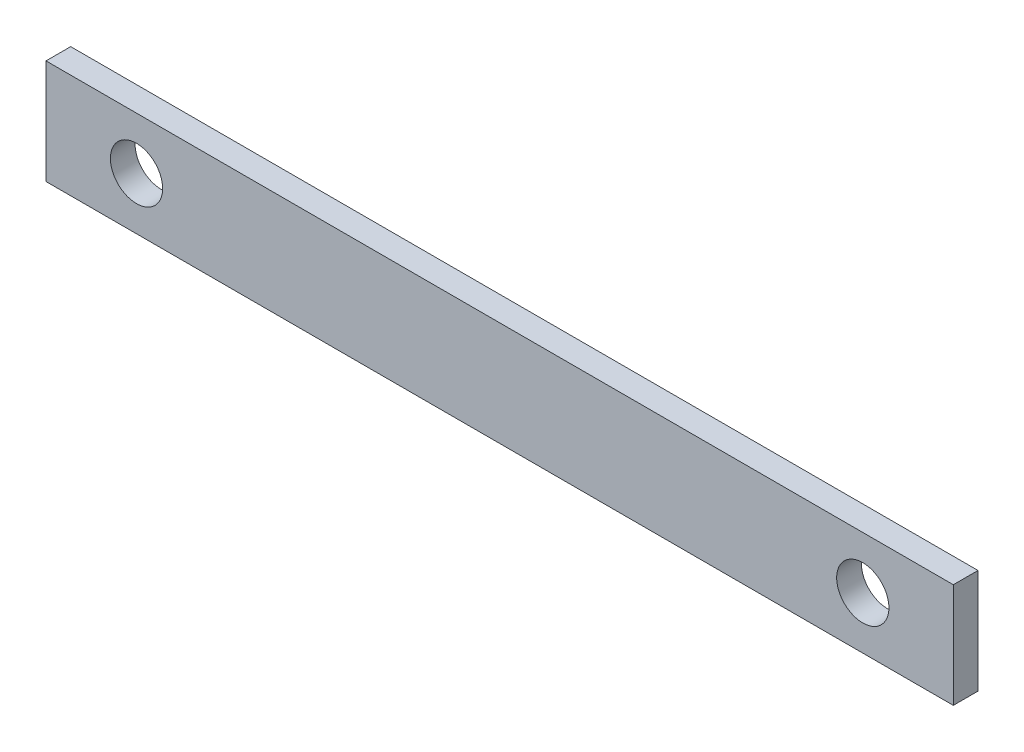
SolidWorks part; units mm, degrees
ref_plane "Alzado" through (0, 0, 0) normal (0, 0, 1) x (1, 0, 0)
ref_plane "Planta" through (0, 0, 0) normal (0, 1, 0) x (1, 0, 0)
ref_plane "Vista lateral" through (0, 0, 0) normal (1, 0, 0) x (0, 0, -1)
sketch "Croquis1" plane through (0, 0, 0) normal (0, 0, 1) x (1, 0, 0)
  line L0 (0, 14.2483) -> (0, -18.3332) construction
  line L1 (55.13, -6.35) -> (-55.13, -6.35)
  line L2 (55.13, -6.35) -> (55.13, 6.35)
  line L3 (55.13, 6.35) -> (-55.13, 6.35)
  line L4 (-55.13, -6.35) -> (-55.13, 6.35)
  line L5 (55.13, -6.35) -> (-55.13, 6.35) construction
  line L6 (55.13, 6.35) -> (-55.13, -6.35) construction
  circle A0 centre (44.13, 0) radius 3.175
  circle A1 centre (-44.13, 0) radius 3.175
  point P0 (0, 0)
  dimension "D3" = 6.35
  dimension "D4" = 11
  dimension "D1" = 110.26
  dimension "D2" = 12.7
extrude "Saliente-Extruir1" add sketch "Croquis1" along normal blind 3
